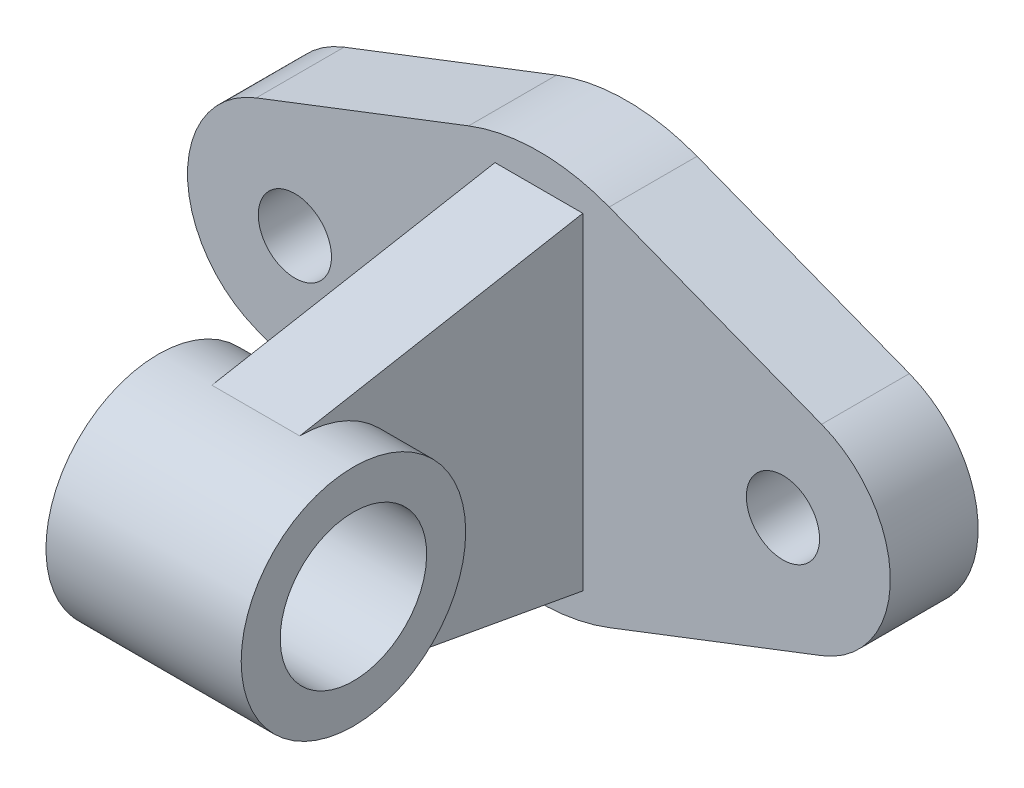
SolidWorks part; units mm, degrees
ref_plane "Front Plane" through (0, 0, 0) normal (0, 0, 1) x (1, 0, 0)
ref_plane "Top Plane" through (0, 0, 0) normal (0, 1, 0) x (1, 0, 0)
ref_plane "Right Plane" through (0, 0, 0) normal (1, 0, 0) x (0, 0, -1)
sketch "Sketch2" plane through (0, 0, 0) normal (0, 0, 1) x (1, 0, 0)
  line L0 (-57.92, 20.525) -> (-14.4, 37.3181)
  line L1 (57.92, 20.525) -> (14.4, 37.3181)
  line L2 (-14.4, -37.3181) -> (-57.92, -20.5249)
  line L3 (14.4, -37.3181) -> (57.92, -20.5249)
  arc A0 (-14.4, -37.3181) -> (14.4, -37.3181) centre (0, 0) ccw
  arc A1 (-57.92, 20.525) -> (-57.92, -20.5249) centre (-50, 0) ccw
  arc A2 (57.92, -20.5249) -> (57.92, 20.525) centre (50, 0) ccw
  arc A3 (14.4, 37.3181) -> (-14.4, 37.3181) centre (0, 0) ccw
  dimension "D1" = 80
  dimension "D2" = 44
  dimension "D3" = 44
  dimension "D4" = 100
  dimension "D5" = 50
extrude "Boss-Extrude1" add sketch "Sketch2" along normal blind 18
sketch "Sketch3" plane through (0, 0, 18) normal (0, 0, 1) x (1, 0, 0)
  line L5 (9, 33.5) -> (-9, 33.5)
  line L6 (9, 33.5) -> (9, -33.5)
  line L7 (9, -33.5) -> (-9, -33.5)
  line L8 (-9, 33.5) -> (-9, -33.5)
  line L9 (9, 33.5) -> (-9, -33.5) construction
  line L10 (9, -33.5) -> (-9, 33.5) construction
  point P0 (0, 0)
  dimension "D1" = 18
  dimension "D2" = 67
extrude "Boss-Extrude2" add sketch "Sketch3" along normal blind 58
sketch "Sketch4" plane through (9, 0, 0) normal (1, 0, 0) x (0, 0, -1)
  line L0 (-76, -33.5) -> (-76, 33.5) construction
  circle A0 centre (-76, 0) radius 23
  dimension "D1" = 46
extrude "Boss-Extrude3" add sketch "Sketch4" against normal blind 29
sketch "Sketch5" plane through (-20, 0, 0) normal (-1, 0, 0) x (0, 0, 1)
  circle A0 centre (76, 0) radius 23
extrude "Boss-Extrude4" add sketch "Sketch5" against normal blind 40
sketch "Sketch6" plane through (20, 0, 0) normal (1, 0, 0) x (0, 0, -1)
  circle A0 centre (-76, 0) radius 15
  dimension "D1" = 30
extrude "Cut-Extrude1" cut sketch "Sketch6" against normal through all
sketch "Sketch7" plane through (9, 0, 0) normal (1, 0, 0) x (0, 0, -1)
  line L0 (-18, -33.5) -> (-76, -23)
  line L1 (-76, -23) -> (-76, -33.5)
  line L2 (-76, -33.5) -> (-18, -33.5)
  line L3 (-18, 33.5) -> (-76, 23)
  line L4 (-76, 23) -> (-76, 33.5)
  line L5 (-76, 33.5) -> (-18, 33.5)
extrude "Cut-Extrude2" cut sketch "Sketch7" against normal through all
sketch "Sketch8" plane through (0, 0, 18) normal (0, 0, 1) x (1, 0, 0)
  circle A0 centre (50, 0) radius 7.5
  circle A1 centre (-50, 0) radius 7.5
  dimension "D1" = 15
  dimension "D2" = 15
extrude "Cut-Extrude3" cut sketch "Sketch8" against normal through all
